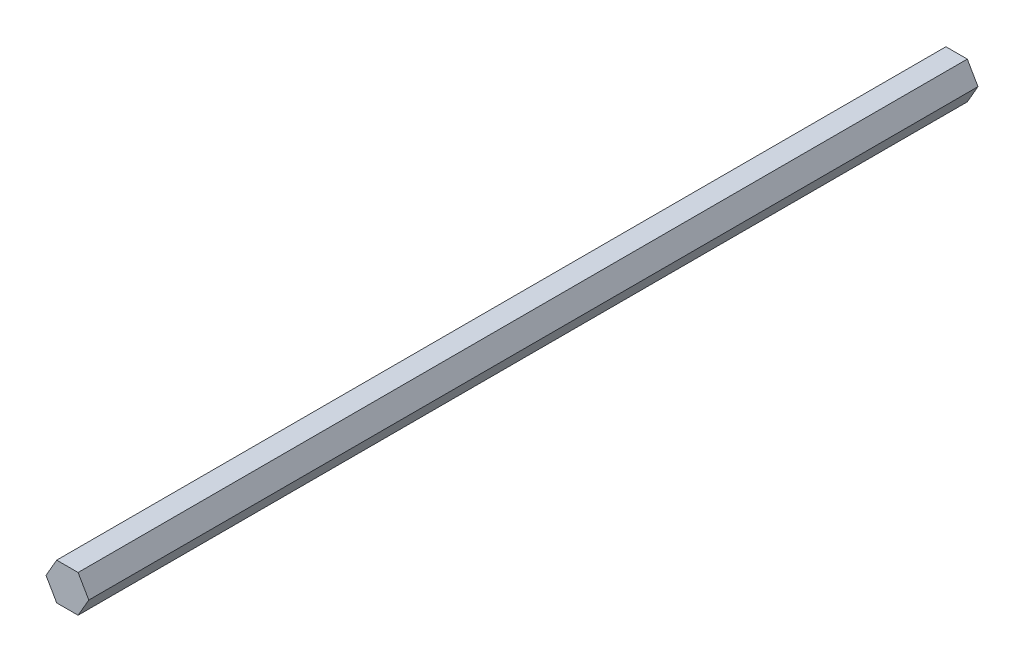
SolidWorks part; units mm, degrees
ref_plane "Front Plane" through (0, 0, 0) normal (0, 0, 1) x (1, 0, 0)
ref_plane "Top Plane" through (0, 0, 0) normal (0, 1, 0) x (1, 0, 0)
ref_plane "Right Plane" through (0, 0, 0) normal (1, 0, 0) x (0, 0, -1)
sketch "Sketch1" plane through (0, 0, 0) normal (0, 0, 1) x (1, 0, 0)
  line L0 (-6.35, -6.35) -> (6.35, 6.35) construction
  line L1 (-6.35, 6.35) -> (6.35, 6.35) construction
  line L2 (-6.35, 6.35) -> (-6.35, -6.35) construction
  line L3 (-6.35, -6.35) -> (6.35, -6.35) construction
  line L4 (6.35, 6.35) -> (6.35, -6.35) construction
  line L10 (7.3323, 0) -> (3.6662, 6.35)
  line L11 (3.6662, 6.35) -> (-3.6662, 6.35)
  line L12 (-3.6662, 6.35) -> (-7.3323, 0)
  line L13 (-7.3323, 0) -> (-3.6662, -6.35)
  line L14 (-3.6662, -6.35) -> (3.6662, -6.35)
  line L15 (3.6662, -6.35) -> (7.3323, 0)
  circle A0 centre (0, 0) radius 6.35 construction
  circle A2 centre (0, 0) radius 6.35 construction
  dimension "WD" = 12.7
  dimension "HT" = 12.7
extrude "Boss-Extrude1" add sketch "Sketch1" along normal mid plane 304.8
